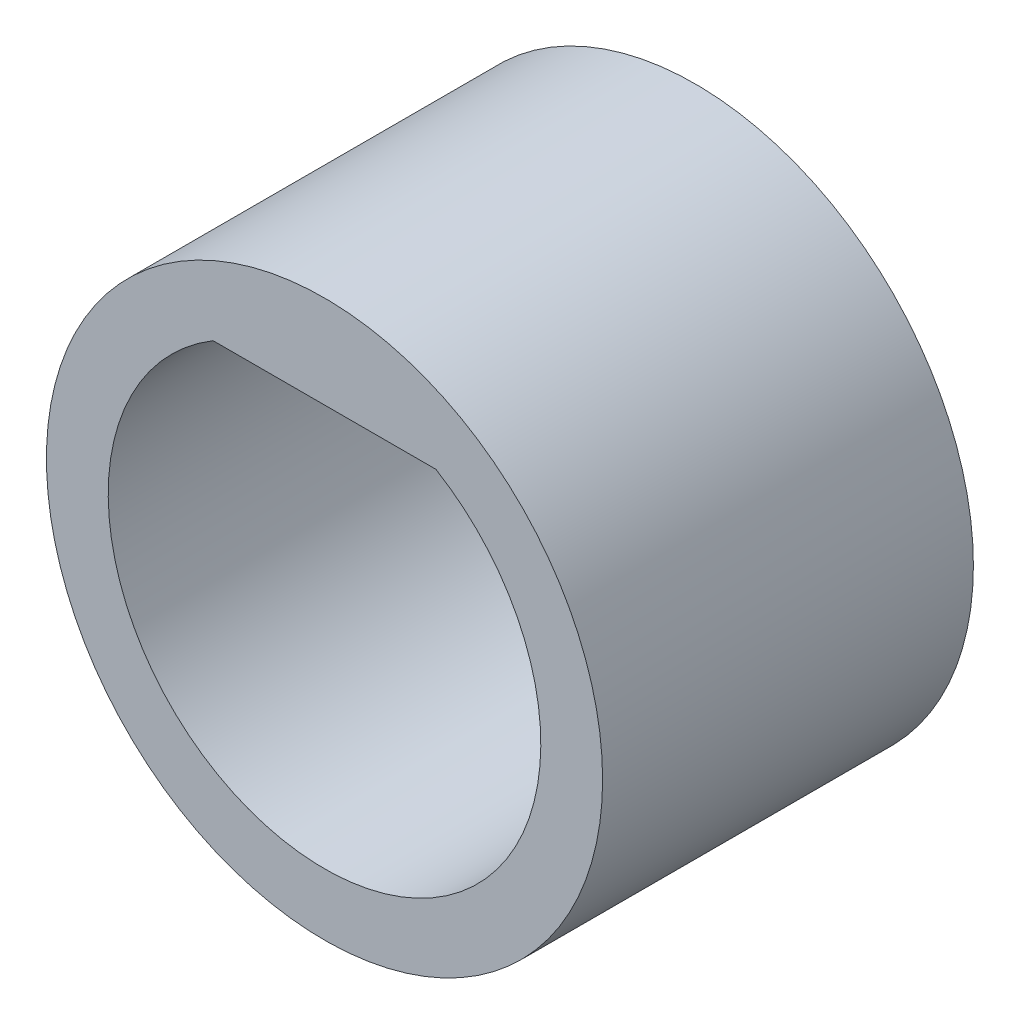
SolidWorks part; units mm, degrees
ref_plane "Front Plane" through (0, 0, 0) normal (0, 0, 1) x (1, 0, 0)
ref_plane "Top Plane" through (0, 0, 0) normal (0, 1, 0) x (1, 0, 0)
ref_plane "Right Plane" through (0, 0, 0) normal (1, 0, 0) x (0, 0, -1)
sketch "Sketch1" plane through (0, 0, 0) normal (0, 0, 1) x (1, 0, 0)
  circle A0 centre (0, 0) radius 4.5
  dimension "D1" = 9
extrude "Boss-Extrude1" add sketch "Sketch1" along normal blind 6
sketch "Sketch2" plane through (0, 0, 6) normal (0, 0, 1) x (1, 0, 0)
  line L0 (-1.8028, 3) -> (1.8028, 3)
  arc A0 (-1.8028, 3) -> (1.8028, 3) centre (0, 0) ccw
  dimension "D1" = 3.5
  dimension "D2" = 3
extrude "Cut-Extrude1" cut sketch "Sketch2" against normal blind 5 and the other way through all
